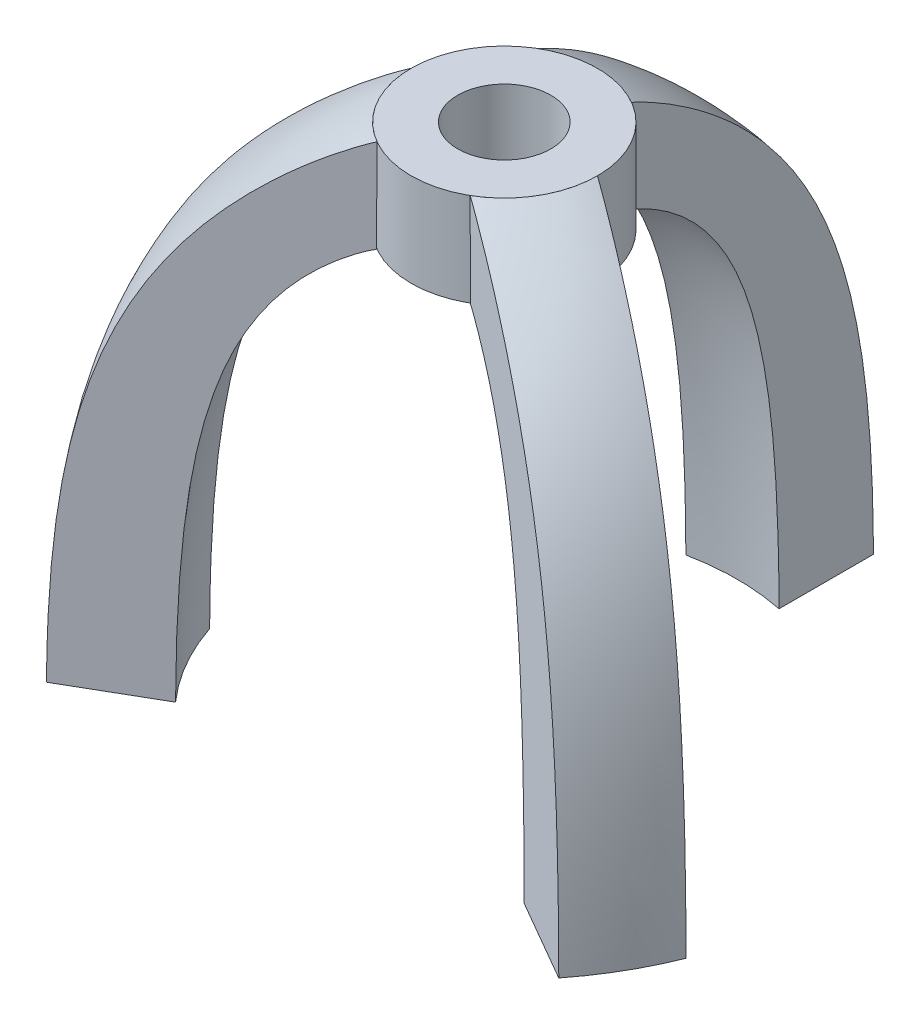
SolidWorks part; units mm, degrees
ref_plane "Front Plane" through (0, 0, 0) normal (0, 0, 1) x (1, 0, 0)
ref_plane "Top Plane" through (0, 0, 0) normal (0, 1, 0) x (1, 0, 0)
ref_plane "Right Plane" through (0, 0, 0) normal (1, 0, 0) x (0, 0, -1)
sketch "Sketch2" plane through (0, 0, 0) normal (0, 1, 0) x (1, 0, 0)
  circle A0 centre (0, 0) radius 6.35
  circle A1 centre (0, 0) radius 3.175
  dimension "D1" = 12.7
  dimension "D2" = 6.35
extrude "Boss-Extrude1" add sketch "Sketch2" along normal blind 6.35
sketch "Sketch6" plane through (0, 0, 0) normal (0, 0, 1) x (1, 0, 0)
  line L0 (15.875, -28.575) -> (22.225, -28.575)
  line L4 (6.35, 6.35) -> (7.4678, 5.7822) construction
  line L5 (7.4678, 5.7822) -> (18.7563, -0.3298) construction
  line L6 (18.7563, -0.3298) -> (22.102, -8.8716) construction
  line L7 (22.102, -8.8716) -> (22.225, -28.575) construction
  line L8 (6.374, 0) -> (7.739, -0.5678) construction
  line L9 (7.739, -0.5678) -> (13.446, -3.8115) construction
  line L10 (6.374, 0) -> (6.35, 6.35)
  line L11 (13.446, -3.8115) -> (15.8103, -9.7298) construction
  line L12 (15.8103, -9.7298) -> (15.875, -28.575) construction
  spline S0 degree 4 poles (6.35, 6.35) (7.4678, 5.7822) (18.7563, -0.3298) (22.102, -8.8716) (22.225, -28.575) knots 0 0 0 0 0 1 1 1 1 1
  spline S1 degree 4 poles (6.374, 0) (7.739, -0.5678) (13.446, -3.8115) (15.8103, -9.7298) (15.875, -28.575) knots 0 0 0 0 0 1 1 1 1 1
  point P19 (19.05, -28.575)
  dimension "D2" = 6.35
  dimension "D3" = 6.35
  dimension "D1" = 19.05
  dimension "D4" = 6.35
  dimension "D5" = 6.35
  dimension "D6" = 34.925
sketch "Sketch7" [suppressed] plane through (0, 0, 0) normal (1, 0, 0) x (0, 0, -1)
  line L0 (0, 0) -> (0, 8.311) construction
revolve "Revolve1" add sketch "Sketch6" angle 360 about L0
sketch "Sketch8" plane through (0, 6.35, 0) normal (0, 1, 0) x (1, 0, 0)
  line L0 (-3.175, 5.4993) -> (-3.175, 22.225)
  line L1 (-3.175, 22.225) -> (3.175, 22.225)
  line L2 (3.175, 22.225) -> (3.175, 5.4993)
  line L3 (6.35, 0) -> (20.8349, -8.3629)
  line L4 (20.8349, -8.3629) -> (17.6599, -13.8621)
  line L5 (17.6599, -13.8621) -> (3.175, -5.4993)
  line L6 (19.2474, -11.1125) -> (0, 0) construction
  line L7 (-3.175, -5.4993) -> (-17.6599, -13.8621)
  line L8 (-17.6599, -13.8621) -> (-20.8349, -8.3629)
  line L9 (-20.8349, -8.3629) -> (-6.35, 0)
  line L10 (0, 0) -> (-19.2474, -11.1125) construction
  circle A0 centre (0, 0) radius 6.35 construction
  circle A1 centre (0, 0) radius 6.35 construction
  circle A2 centre (0, 0) radius 22.225 construction
  circle A3 centre (0, 0) radius 22.225
  point P4 (0, 22.225)
  point P9 (19.2474, -11.1125)
  circle M11 centre (0, 0) radius 6.35
  dimension "D1" = 6.35
  dimension "D2" = 120
  dimension "D3" = 120
  dimension "D4" = 120
  dimension "D5" = 120
extrude "Cut-Extrude1" cut sketch "Sketch8" against normal through all contours L0 A3 L9 M11 | L3 A3 L2 M11 | L7 A3 L5 M11
